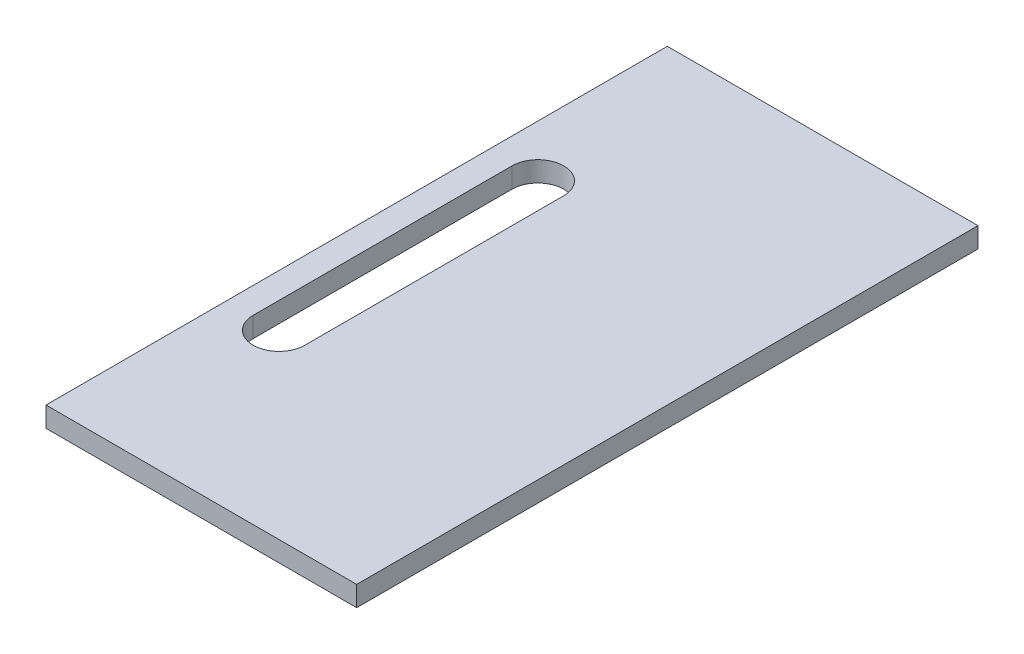
SolidWorks part; units mm, degrees
ref_plane "Front Plane" through (0, 0, 0) normal (0, 0, 1) x (1, 0, 0)
ref_plane "Top Plane" through (0, 0, 0) normal (0, 1, 0) x (1, 0, 0)
ref_plane "Right Plane" through (0, 0, 0) normal (1, 0, 0) x (0, 0, -1)
sketch "Sketch1" plane through (0, 0, 0) normal (0, 1, 0) x (1, 0, 0)
  line L1 (0, 0) -> (304.8, 0)
  line L2 (0, 0) -> (0, 609.6)
  line L3 (0, 609.6) -> (304.8, 609.6)
  line L4 (304.8, 0) -> (304.8, 609.6)
  dimension "D1" = 304.8
  dimension "D2" = 609.6
extrude "Boss-Extrude1" add sketch "Sketch1" along normal blind 19.8438
sketch "Sketch2" plane through (0, 19.8438, 0) normal (0, 1, 0) x (1, 0, 0)
  line L0 (50.8, 431.8) -> (50.8, 177.8) construction
  line L1 (76.2, 431.8) -> (76.2, 177.8)
  line L2 (25.4, 431.8) -> (25.4, 177.8)
  line L3 (304.8, 0) -> (304.8, 609.6) construction
  line L4 (0, 304.8) -> (304.8, 304.8) construction
  line L5 (0, 609.6) -> (0, 0) construction
  arc A0 (76.2, 431.8) -> (25.4, 431.8) centre (50.8, 431.8) ccw
  arc A1 (25.4, 177.8) -> (76.2, 177.8) centre (50.8, 177.8) ccw
  point P2 (50.8, 304.8)
  point P13 (0, 0)
  point P14 (50.8, 182.6122)
  dimension "D3" = 25.4
  dimension "D1" = 254
  dimension "D2" = 254
extrude "Cut-Extrude1" cut sketch "Sketch2" against normal through all
equation "\"2f\"=16.5455"
